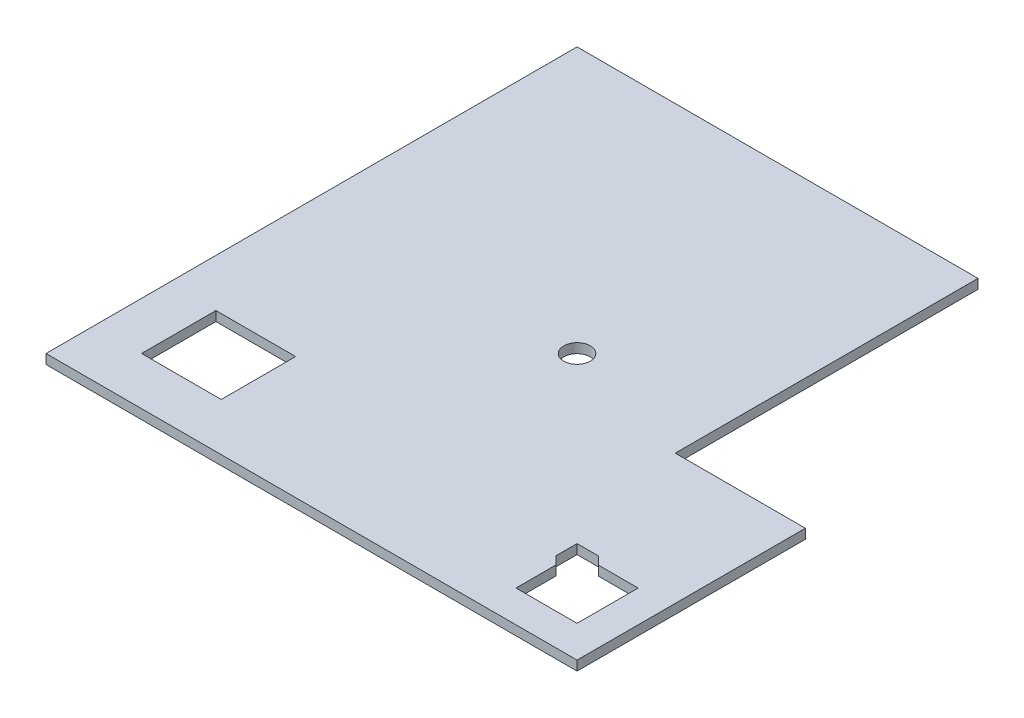
SolidWorks part; units mm, degrees
material "Teak"
ref_plane "Front Plane" through (0, 0, 0) normal (0, 0, 1) x (1, 0, 0)
ref_plane "Top Plane" through (0, 0, 0) normal (0, 1, 0) x (1, 0, 0)
ref_plane "Right Plane" through (0, 0, 0) normal (1, 0, 0) x (0, 0, -1)
sketch "Sketch1" plane through (0, 0, 0) normal (0, 1, 0) x (1, 0, 0)
  line L0 (0, 0) -> (1000, 0)
  line L3 (755, 430) -> (755, 1000)
  line L4 (755, 1000) -> (0, 1000)
  line L5 (0, 1000) -> (0, 0)
  line L7 (1000, 0) -> (1000, 430)
  line L9 (1000, 430) -> (755, 430)
  dimension "D1" = 1000
  dimension "D2" = 1000
  dimension "D3" = 90
  dimension "D4" = 755
  dimension "D5" = 570
  dimension "D6" = 90
extrude "Boss-Extrude1" add sketch "Sketch1" along normal blind 18
sketch "Sketch3" plane through (0, 18, 0) normal (0, 1, 0) x (1, 0, 0)
  line L0 (50, 950) -> (50, 50) construction
  line L1 (240, 90) -> (90, 90)
  line L2 (240, 90) -> (240, 230)
  line L3 (240, 230) -> (90, 230)
  line L4 (90, 90) -> (90, 230)
  line L5 (50, 50) -> (520, 50) construction
  dimension "D1" = 150
  dimension "D2" = 140
  dimension "D3" = 40
  dimension "D4" = 40
extrude "Cut-Extrude2" cut sketch "Sketch3" against normal up to surface (18 mm away) up to face at (585, 0, -476.6667)
sketch "Sketch4" plane through (0, 18, 0) normal (0, 1, 0) x (1, 0, 0)
  line L0 (940, 60) -> (940, 175)
  line L1 (940, 60) -> (825, 60)
  line L2 (810, 150) -> (810, 190)
  line L3 (850, 190) -> (810, 190)
  line L4 (825, 60) -> (825, 135)
  line L5 (825, 135) -> (810, 150)
  line L6 (850, 190) -> (865, 175)
  line L7 (865, 175) -> (940, 175)
  line L8 (1000, 0) -> (1000, 430) construction
  line L10 (0, 0) -> (1000, 0) construction
  dimension "D1" = 115
  dimension "D2" = 75
  dimension "D3" = 21.2132
  dimension "D4" = 40
  dimension "D5" = 40
  dimension "D6" = 21.2132
  dimension "D7" = 75
  dimension "D8" = 115
  dimension "D9" = 135
  dimension "D10" = 135
  dimension "D11" = 60
  dimension "D12" = 60
extrude "Cut-Extrude3" cut sketch "Sketch4" against normal up to surface (18 mm away) up to face at (165, 0, -160)
sketch "Sketch5" plane through (0, 18, 0) normal (0, 1, 0) x (1, 0, 0)
  line L1 (0, 0) -> (1000, 0) construction
  line L2 (0, 1000) -> (0, 0) construction
  circle A0 centre (500, 500) radius 25
  dimension "D3" = 50
  dimension "D1" = 500
  dimension "D2" = 500
extrude "Cut-Extrude4" cut sketch "Sketch5" against normal through all
